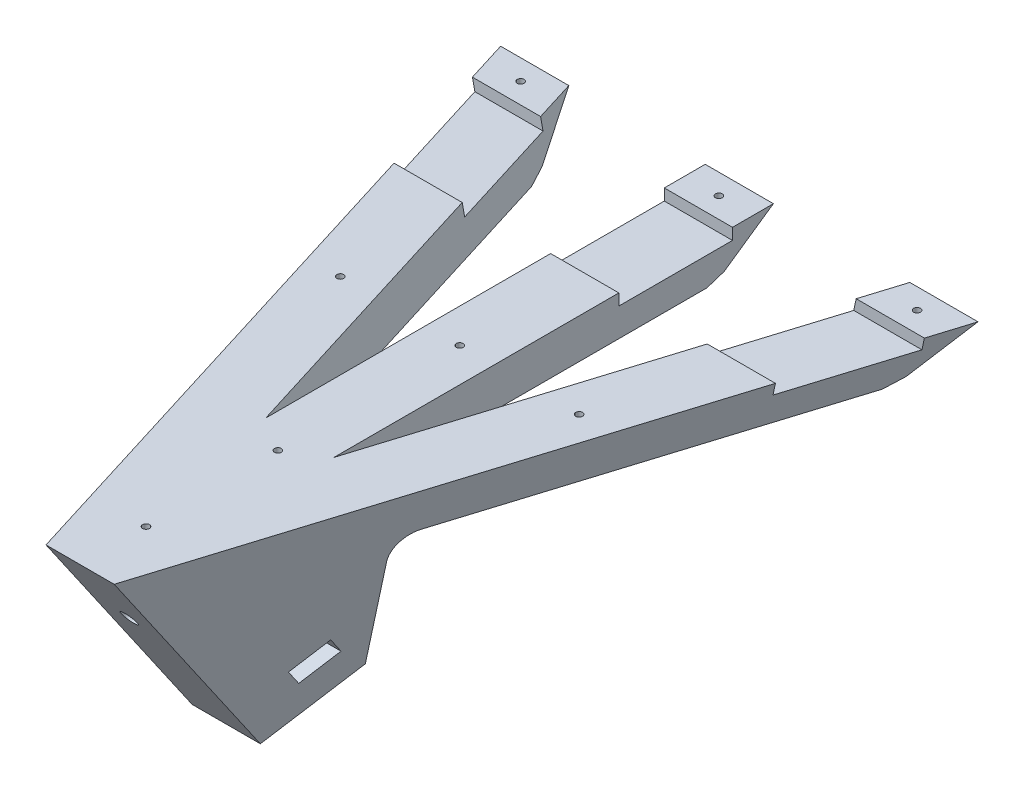
SolidWorks part; units mm, degrees
ref_plane "Alzado" through (0, 0, 0) normal (0, 0, 1) x (1, 0, 0)
ref_plane "Planta" through (0, 0, 0) normal (0, 1, 0) x (1, 0, 0)
ref_plane "Vista lateral" through (0, 0, 0) normal (1, 0, 0) x (0, 0, -1)
sketch "Croquis2" plane through (0, 0, 0) normal (0, 1, 0) x (1, 0, 0)
  line L1 (195, 145) -> (-195, 145)
  line L2 (195, 145) -> (195, -145)
  line L3 (195, -145) -> (-195, -145)
  line L4 (-195, 145) -> (-195, -145)
  line L5 (195, 145) -> (-195, -145) construction
  line L6 (195, -145) -> (-195, 145) construction
  point P0 (0, 0)
extrude "Saliente-Extruir2" add sketch "Croquis2" along normal blind 10
sketch "Croquis3" plane through (0, 10, 0) normal (0, 1, 0) x (1, 0, 0)
  line L0 (195, -145) -> (195, 145) construction
  line L1 (-195, -145) -> (195, -145)
  line L2 (-195, -145) -> (-195, -138)
  line L3 (-195, -138) -> (195, -138)
  line L4 (195, -145) -> (195, -138)
extrude "Saliente-Extruir3" add sketch "Croquis3" along normal blind 25
sketch "Croquis5" plane through (-195, 0, 0) normal (-1, 0, 0) x (0, 0, 1)
  line L0 (145, 0) -> (51.1207, -135.6896)
  line L2 (51.1207, -135.6896) -> (-145, 0)
  line L3 (-145, 0) -> (145, 0)
  dimension "D1" = 165
  dimension "D2" = 90
extrude "Saliente-Extruir4" add sketch "Croquis5" against normal blind 390
sketch "Croquis6" plane through (-195, 0, 0) normal (-1, 0, 0) x (0, 0, 1)
  line L0 (-145, 0) -> (145, 0)
  line L1 (145, 0) -> (51.1207, -135.6896)
  line L2 (51.1207, -135.6896) -> (-145, 0)
extrude "Cortar-Extruir1" cut sketch "Croquis6" against normal blind 180
sketch "Croquis7" plane through (195, 0, 0) normal (1, 0, 0) x (0, 0, -1)
  line L0 (145, 0) -> (-145, 0)
  line L1 (-145, 0) -> (-51.1207, -135.6896)
  line L2 (-51.1207, -135.6896) -> (145, 0)
extrude "Cortar-Extruir2" cut sketch "Croquis7" against normal blind 180
sketch "Croquis8" plane through (0, -67.8448, -46.9397) normal (0, -0.8224, -0.569) x (-1, 0, 0)
  line L0 (15, -119.2424) -> (105, 119.2424)
  line L1 (15, 119.2424) -> (195, 119.2424) construction
  line L2 (105, 119.2424) -> (75, 119.2424)
  line L3 (75, 119.2424) -> (15, -39.7475)
  line L4 (15, 119.2424) -> (15, -119.2424) construction
  line L5 (15, -39.7475) -> (15, -119.2424)
extrude "Saliente-Extruir5" add sketch "Croquis8" against normal blind 179
sketch "Croquis10" plane through (-195, 0, 0) normal (-1, 0, 0) x (0, 0, 1)
  line L0 (138, 35) -> (138, 10) construction
  line L1 (-145, 10) -> (138, 10)
  line L2 (-145, 10) -> (-145, 204.11)
  line L3 (-145, 204.11) -> (138, 204.11)
  line L4 (138, 10) -> (138, 204.11)
  dimension "D1" = 0
extrude "Cortar-Extruir5" cut sketch "Croquis10" against normal blind 236
sketch "Croquis11" plane through (-195, 0, 0) normal (-1, 0, 0) x (0, 0, 1)
  line L0 (145, 17.0241) -> (145, 0)
  line L1 (145, 0) -> (165.7896, 1.6032)
  line L2 (165.7896, 1.6032) -> (161.3582, 19.3089)
  line L3 (161.3582, 19.3089) -> (145, 17.0241)
extrude "Cortar-Extruir6" cut sketch "Croquis11" against normal blind 236
sketch "Croquis12" plane through (0, -67.8448, -46.9397) normal (0, -0.8224, -0.569) x (-1, 0, 0)
  line L0 (-15, -119.2424) -> (-105, 119.2424)
  line L1 (-195, 119.2424) -> (-15, 119.2424) construction
  line L2 (-105, 119.2424) -> (-75, 119.2424)
  line L3 (-75, 119.2424) -> (-15, -39.7475)
  line L4 (-15, -119.2424) -> (-15, 119.2424) construction
  line L5 (-15, -39.7475) -> (-15, -119.2424)
extrude "Saliente-Extruir6" add sketch "Croquis12" against normal blind 236
sketch "Croquis13" plane through (195, 0, 0) normal (1, 0, 0) x (0, 0, -1)
  line L1 (-138, 10) -> (201.7989, 10)
  line L2 (-138, 10) -> (-138, 246.8197)
  line L3 (-138, 246.8197) -> (201.7989, 246.8197)
  line L4 (201.7989, 10) -> (201.7989, 246.8197)
  line L5 (-145, 0) -> (-189.7765, 0)
  line L6 (-145, 0) -> (-145, 75.1047)
  line L7 (-145, 75.1047) -> (-189.7765, 75.1047)
  line L8 (-189.7765, 0) -> (-189.7765, 75.1047)
extrude "Cortar-Extruir7" cut sketch "Croquis13" against normal blind 500
sketch "Croquis14" plane through (195, 0, 0) normal (1, 0, 0) x (0, 0, -1)
  line L1 (-138, 35) -> (-197.446, 35)
  line L2 (-138, 35) -> (-138, 116.4359)
  line L3 (-138, 116.4359) -> (-197.446, 116.4359)
  line L4 (-197.446, 35) -> (-197.446, 116.4359)
extrude "Cortar-Extruir8" cut sketch "Croquis14" against normal blind 500
sketch "Croquis15" plane through (-195, 0, 0) normal (-1, 0, 0) x (0, 0, 1)
  line L0 (-145, 0) -> (145, 0) construction
  line L1 (-127, 0) -> (-77, 0)
  line L2 (-127, 0) -> (-127, -5)
  line L3 (-127, -5) -> (-77, -5)
  line L4 (-77, 0) -> (-77, -5)
  line L6 (138, 35) -> (138, 10) construction
  dimension "D1" = 50
  dimension "D2" = 215
  dimension "D3" = 5
extrude "Cortar-Extruir9" cut sketch "Croquis15" against normal blind 500
sketch "Croquis16" plane through (0, 10, 0) normal (0, 1, 0) x (1, 0, 0)
  line L1 (-195, 145) -> (195, 145)
  line L2 (-195, 145) -> (-195, -138)
  line L3 (-195, -138) -> (195, -138)
  line L4 (195, 145) -> (195, -138)
extrude "Cortar-Extruir10" cut sketch "Croquis16" against normal blind 10
sketch "Croquis17" plane through (0, 0, 0) normal (0, 1, 0) x (1, 0, 0)
  line L0 (-99.4138, 127) -> (-99.4138, 145) construction
  line L1 (-105, 145) -> (-75, 145) construction
  line L2 (-75, 145) -> (-75, 127) construction
  line L3 (-69.4138, 127) -> (-99.4138, 127) construction
  line L5 (15, 145) -> (-15, 145) construction
  line L6 (75, 145) -> (105, 145) construction
  circle A0 centre (-87.205, 136) radius 3.75
  circle A1 centre (0, 136) radius 3.75
  circle A2 centre (87.205, 136) radius 3.75
  dimension "D1" = 9
  dimension "D2" = 7.5
  dimension "D7" = 7.5
  dimension "D8" = 7.5
  dimension "D3" = 9
  dimension "D4" = 12.205
  dimension "D5" = 12.205
  dimension "D6" = 9
extrude "Cortar-Extruir11" cut sketch "Croquis17" against normal blind 10
sketch "Croquis18" plane through (0, 0, 0) normal (0, 1, 0) x (1, 0, 0)
  circle A0 centre (-87.205, 136) radius 1.5
  circle A1 centre (-87.205, 136) radius 3.75
  circle A2 centre (0, 136) radius 3.75
  circle A3 centre (0, 136) radius 1.5
  circle A4 centre (87.205, 136) radius 1.5
  circle A5 centre (87.205, 136) radius 3.75
extrude "Saliente-Extruir8" add sketch "Croquis18" against normal blind 4
sketch "Croquis19" plane through (0, 0, 0) normal (0, 1, 0) x (1, 0, 0)
  line L0 (-15, -48.3333) -> (-53.8966, 77) construction
  line L1 (53.8966, 77) -> (15, -48.3333) construction
  line L2 (-17.1724, -138) -> (17.1724, -138) construction
  circle A0 centre (-52.5333, 22) radius 1.5
  circle A1 centre (0, 22) radius 1.5
  circle A2 centre (52.5333, 22) radius 1.5
  circle A3 centre (0, -58) radius 1.5
  circle A4 centre (0, -116) radius 1.5
  dimension "D1" = 15
  dimension "D2" = 15
  dimension "D6" = 80
  dimension "D7" = 3
  dimension "D3" = 160
  dimension "D4" = 0
  dimension "D5" = 0
  dimension "D8" = 22
extrude "Saliente-Extruir10" add sketch "Croquis19" along normal blind 15
sketch "Croquis20" plane through (0, 0, 0) normal (0, 1, 0) x (1, 0, 0)
  circle A0 centre (-87.205, 136) radius 1.5
  circle A1 centre (0, 136) radius 1.5
  circle A2 centre (87.205, 136) radius 1.5
extrude "Saliente-Extruir11" add sketch "Croquis20" along normal blind 15 separate body
sketch "Croquis21" plane through (0, 0, 0) normal (0, 1, 0) x (1, 0, 0)
  line L1 (-195, -138) -> (195, -138)
  line L2 (-195, -138) -> (-195, 145)
  line L3 (-195, 145) -> (195, 145)
  line L4 (195, -138) -> (195, 145)
extrude "Saliente-Extruir12" add sketch "Croquis21" along normal blind 10
sketch "Croquis22" plane through (0, 15, 0) normal (0, 1, 0) x (1, 0, 0)
  circle A0 centre (0, -116) radius 1.5
  circle A1 centre (0, -58) radius 1.5
  circle A2 centre (-52.5333, 22) radius 1.5
  circle A3 centre (0, 22) radius 1.5
  circle A4 centre (52.5333, 22) radius 1.5
  circle A5 centre (87.205, 136) radius 1.5
  circle A6 centre (0, 136) radius 1.5
  circle A7 centre (-87.205, 136) radius 1.5
extrude "Cortar-Extruir12" cut sketch "Croquis22" against normal blind 47
sketch "Croquis26" plane through (-195, 0, 0) normal (-1, 0, 0) x (0, 0, 1)
  line L1 (-145, 10) -> (138, 10)
  line L2 (-145, 10) -> (-145, 5.5)
  line L3 (-145, 5.5) -> (138, 5.5)
  line L4 (138, 10) -> (138, 5.5)
extrude "Cortar-Extruir16" cut sketch "Croquis26" against normal blind 500
sketch "Croquis27" plane through (-195, 0, 0) normal (-1, 0, 0) x (0, 0, 1)
  line L0 (145, 35) -> (145, 0) construction
  line L1 (138, 35) -> (145, 35)
  line L2 (138, 35) -> (138, 25.5)
  line L3 (138, 25.5) -> (145, 25.5)
  line L4 (145, 35) -> (145, 25.5)
  line L5 (-145, 5.5) -> (138, 5.5) construction
  dimension "D1" = 20
extrude "Cortar-Extruir17" cut sketch "Croquis27" against normal blind 500
sketch "Croquis28" plane through (-195, 0, 0) normal (-1, 0, 0) x (0, 0, 1)
  line L0 (51.1207, -135.6896) -> (80.7069, -92.9268)
  line L1 (51.1207, -135.6896) -> (19.4598, -113.7845)
  line L2 (80.7069, -92.9268) -> (49.046, -71.0217)
  line L3 (19.4598, -113.7845) -> (49.046, -71.0217)
  line L4 (51.1207, -135.6896) -> (145, 0) construction
  dimension "D1" = 113
  dimension "D2" = 38.5
extrude "Cortar-Extruir18" cut sketch "Croquis28" against normal blind 500
sketch "Croquis29" plane through (0, -25.082, -17.3534) normal (0, -0.8224, -0.569) x (-1, 0, 0)
  line L0 (-15, -119.2424) -> (15, -119.2424) construction
  circle A0 centre (0, -91.2424) radius 3.5
  dimension "D1" = 28
extrude "Cortar-Extruir19" cut sketch "Croquis29" against normal blind 20
sketch "Croquis31" plane through (195, 0, 0) normal (1, 0, 0) x (0, 0, -1)
  line L0 (-71.4506, -70.7146) -> (-76.0024, -64.1357)
  line L1 (-71.4506, -70.7146) -> (-58.704, -61.8956)
  line L2 (-76.0024, -64.1357) -> (-63.2558, -55.3167)
  line L3 (-58.704, -61.8956) -> (-63.2558, -55.3167)
  line L6 (-49.046, -71.0217) -> (-80.7069, -92.9268) construction
  line L7 (-145, 0) -> (-80.7069, -92.9268) construction
  point P4 (-69.6291, -59.7262)
  dimension "D1" = 13
  dimension "D2" = 8
  dimension "D3" = 15.5
  dimension "D4" = 28
extrude "Cortar-Extruir20" cut sketch "Croquis31" against normal blind 314
sketch "Croquis32" plane through (0, -67.8448, 98.0603) normal (0, -0.569, 0.8224) x (1, 0, 0)
  line L0 (-15, 82.5) -> (15, 82.5) construction
  circle A0 centre (0, 47.5) radius 3.5
  dimension "D1" = 35
extrude "Cortar-Extruir21" cut sketch "Croquis32" against normal blind 25
sketch "Croquis33" plane through (195, 0, 0) normal (1, 0, 0) x (0, 0, -1)
  line L1 (-145, 0) -> (163.8337, 0)
  line L2 (-145, 0) -> (-145, 37.0388)
  line L3 (-145, 37.0388) -> (163.8337, 37.0388)
  line L4 (163.8337, 0) -> (163.8337, 37.0388)
extrude "Cortar-Extruir22" cut sketch "Croquis33" against normal blind 500
sketch "Croquis34" plane through (0, 0, 0) normal (0, 1, 0) x (1, 0, 0)
  line L1 (-195, 145) -> (195, 145)
  line L2 (-195, 145) -> (-195, -145)
  line L3 (-195, -145) -> (195, -145)
  line L4 (195, 145) -> (195, -145)
  line L5 (-195, 145) -> (195, -145) construction
  line L6 (-195, -145) -> (195, 145) construction
  circle A0 centre (0, -58) radius 1.5
  circle A1 centre (0, -116) radius 1.5
  circle A2 centre (-52.5333, 22) radius 1.5
  circle A3 centre (0, 22) radius 1.5
  circle A4 centre (52.5333, 22) radius 1.5
  circle A5 centre (-87.205, 136) radius 1.5
  circle A6 centre (0, 136) radius 1.5
  circle A7 centre (87.205, 136) radius 1.5
  point P0 (0, 0)
extrude "Saliente-Extruir14" add sketch "Croquis34" along normal blind 5.5
sketch "Croquis35" plane through (0, 5.5, 0) normal (0, 1, 0) x (1, 0, 0)
  line L1 (-195, -145) -> (195, -145)
  line L2 (-195, -145) -> (-195, -135)
  line L3 (-195, -135) -> (195, -135)
  line L4 (195, -145) -> (195, -135)
extrude "Saliente-Extruir15" add sketch "Croquis35" along normal blind 22
sketch "Croquis36" plane through (-195, 0, 0) normal (-1, 0, 0) x (0, 0, 1)
  line L0 (-123.3196, -5) -> (-123.3196, -15)
  line L1 (-127, -5) -> (-77, -5) construction
  line L2 (19.4598, -113.7845) -> (-145, 0) construction
  line L3 (-123.3196, -15) -> (49.046, -71.0217)
  line L4 (49.046, -71.0217) -> (19.4598, -113.7845)
  line L5 (19.4598, -113.7845) -> (-123.3196, -15)
  dimension "D1" = 10
extrude "Cortar-Extruir23" cut sketch "Croquis36" against normal blind 488 contours L5 L4 L3
sketch "Croquis37" plane through (-195, 0, 0) normal (-1, 0, 0) x (0, 0, 1)
  line L3 (-115.7721, -5) -> (-115.7721, -17.453) construction
  line L4 (-127, -5) -> (-77, -5) construction
  line L5 (-123.3196, -15) -> (49.046, -71.0217) construction
  line L6 (-115.7721, -17.453) -> (39.046, -17.453)
  line L7 (49.046, -71.0217) -> (49.046, -27.453)
  line L8 (-115.7721, -17.453) -> (49.046, -71.0217)
  arc A1 (49.046, -27.453) -> (39.046, -17.453) centre (39.046, -27.453) ccw
  dimension "D1" = 12.453
  dimension "D3" = 90
  dimension "D4" = 90
extrude "Cortar-Extruir28" cut sketch "Croquis37" against normal blind 479.5
sketch "Croquis38" plane through (0, -67.8448, 98.0603) normal (0, -0.569, 0.8224) x (1, 0, 0)
  circle A0 centre (0, 44.5) radius 3.5
  circle A1 centre (0, 47.5) radius 3.5 construction
  dimension "D1" = 3
extrude "Cortar-Extruir29" cut sketch "Croquis38" against normal blind 25
sketch "Croquis39" plane through (0, -32, 0) normal (0, 1, 0) x (1, 0, 0)
  circle A0 centre (0, -116) radius 1.5
extrude "Saliente-Extruir16" add sketch "Croquis39" along normal blind 9
sketch "Croquis40" plane through (0, -67.8448, 98.0603) normal (0, -0.569, 0.8224) x (1, 0, 0)
  circle A0 centre (0, 47.5) radius 3.5
extrude "Saliente-Extruir17" add sketch "Croquis40" against normal blind 25
sketch "Croquis41" plane through (0, -67.8448, 98.0603) normal (0, -0.569, 0.8224) x (1, 0, 0)
  circle A0 centre (0, 44.5) radius 3.5
extrude "Cortar-Extruir30" cut sketch "Croquis41" against normal blind 25
sketch "Croquis42" plane through (0, 5.5, 0) normal (0, 1, 0) x (1, 0, 0)
  line L1 (-195, 145) -> (195, 145)
  line L2 (-195, 145) -> (-195, -145)
  line L3 (-195, -145) -> (195, -145)
  line L4 (195, 145) -> (195, -145)
extrude "Cortar-Extruir31" cut sketch "Croquis42" along normal blind 41 and the other way blind 5.5
